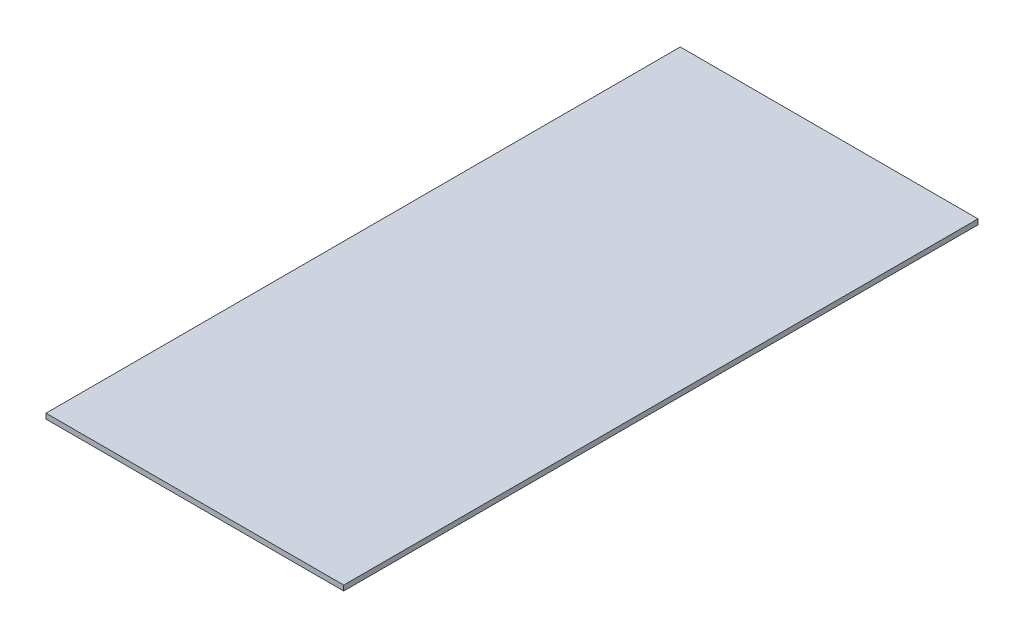
SolidWorks part; units mm, degrees
material "Glass"
ref_plane "Front Plane" through (0, 0, 0) normal (0, 0, 1) x (1, 0, 0)
ref_plane "Top Plane" through (0, 0, 0) normal (0, 1, 0) x (1, 0, 0)
ref_plane "Right Plane" through (0, 0, 0) normal (1, 0, 0) x (0, 0, -1)
sketch "Sketch1" plane through (0, 0, 0) normal (0, 1, 0) x (1, 0, 0)
  line L1 (-230, -490) -> (230, -490)
  line L2 (-230, -490) -> (-230, 490)
  line L3 (-230, 490) -> (230, 490)
  line L4 (230, -490) -> (230, 490)
  line L5 (-230, -490) -> (230, 490) construction
  line L6 (-230, 490) -> (230, -490) construction
  point P0 (0, 0)
  dimension "D1" = 980
  dimension "D2" = 460
extrude "Boss-Extrude1" add sketch "Sketch1" along normal mid plane 8
sketch "Sketch2" plane through (0, -4, 0) normal (0, -1, 0) x (1, 0, 0)
  line L6 (18, -450) -> (120, -450)
  line L7 (18, -450) -> (18, -230)
  line L8 (200, 400) -> (-200, 400)
  line L9 (120, -450) -> (120, -230)
  line L10 (-200, 50) -> (-200, 400)
  line L11 (0, 0) -> (0, 400) construction
  line L12 (69, -643.883) -> (69, -450) construction
  line L13 (69, -352.7148) -> (69, -350.5148) construction
  line L14 (18, -230) -> (120, -230)
  line L15 (-200, 50) -> (200, 50)
  line L16 (200, 50) -> (200, 400)
  point P14 (0, 0)
  point P16 (0, 0)
  dimension "D1" = 450
  dimension "D2" = 120
  dimension "D3" = 230
  dimension "D4" = 102
  dimension "D5" = 400
  dimension "D6" = 50
  dimension "D7" = 400
split line "Split Line1"
